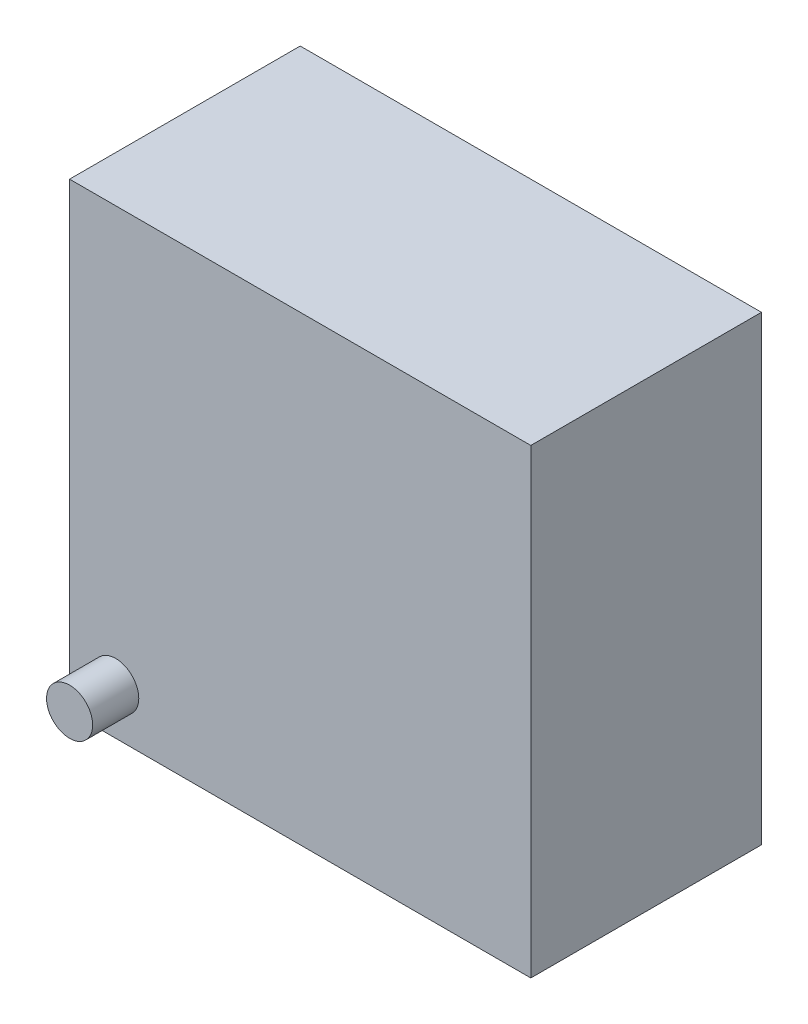
SolidWorks part; units mm, degrees
ref_plane "前视基准面" through (0, 0, 0) normal (0, 0, 1) x (1, 0, 0)
ref_plane "上视基准面" through (0, 0, 0) normal (0, 1, 0) x (1, 0, 0)
ref_plane "右视基准面" through (0, 0, 0) normal (1, 0, 0) x (0, 0, -1)
other "Configuration Table"
sketch "草图1" plane through (0, 0, 0) normal (0, 0, 1) x (1, 0, 0)
  line L1 (0, 0) -> (20, 0)
  line L2 (0, 0) -> (0, 20)
  line L3 (0, 20) -> (20, 20)
  line L4 (20, 0) -> (20, 20)
extrude "BaseBox" add sketch "草图1" along normal blind 10
sketch "草图2" plane through (0, 0, 10) normal (0, 0, 1) x (1, 0, 0)
  circle A0 centre (2, 2) radius 1
extrude "BossSeed" add sketch "草图2" along normal blind 2
pattern_circular "CircularPattern" count 4 over 360 about axis through (0, 0, 10) along (0, 0, -1) of "BossSeed"
